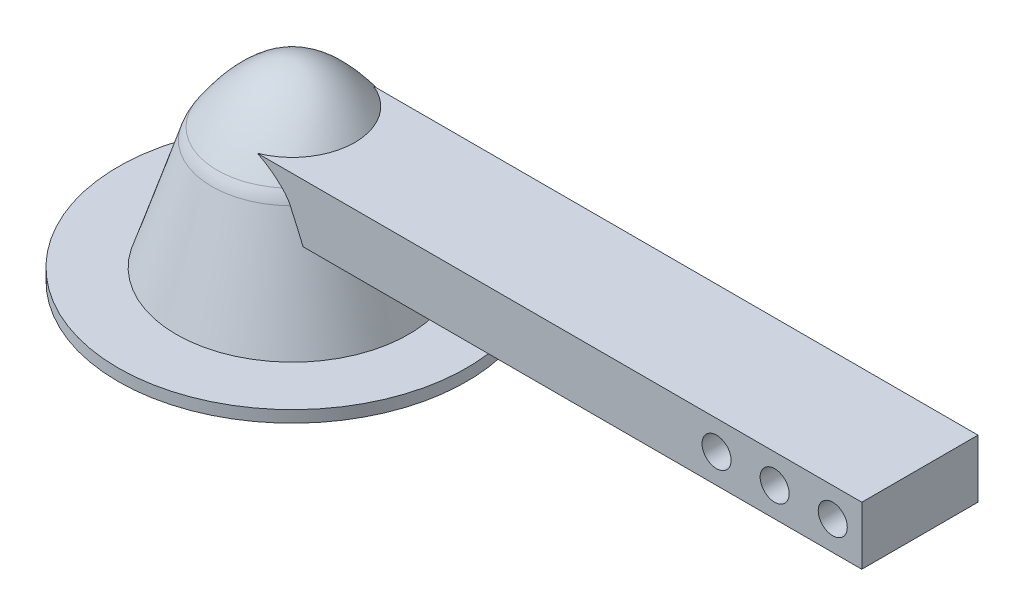
SolidWorks part; units mm, degrees
material "1060 Alloy"
ref_plane "Front Plane" through (0, 0, 0) normal (0, 0, 1) x (1, 0, 0)
ref_plane "Top Plane" through (0, 0, 0) normal (0, 1, 0) x (1, 0, 0)
ref_plane "Right Plane" through (0, 0, 0) normal (1, 0, 0) x (0, 0, -1)
sketch "Sketch1" plane through (0, 0, 0) normal (0, 0, 1) x (1, 0, 0)
  line L0 (0, 27.7021) -> (0, -45.7364) construction
  line L1 (-59.1227, 0) -> (59.4945, 0) construction
  line L2 (0, 20.093) -> (25.4, 20.093)
  line L3 (25.4, 20.093) -> (25.4, 13.743)
  line L4 (25.4, 13.743) -> (0, 13.743)
  line L5 (25.4, 20.093) -> (38.1, 20.093)
  line L6 (38.1, 20.093) -> (38.1, 22.6646)
  line L7 (38.1, 22.6646) -> (0, 22.6646)
  line L8 (0, 22.6646) -> (0, 13.743)
  line L9 (25.4, 22.6646) -> (17.2297, 48.0481)
  line L10 (17.2297, 48.0481) -> (0, 48.0481)
  line L11 (0, 48.0481) -> (0, 22.6646)
  dimension "D1" = 25.4
  dimension "D2" = 6.35
  dimension "D3" = 12.7
  dimension "D4" = 2.5716
  dimension "D5" = 25.4
revolve "Revolve1" add sketch "Sketch1" angle 360 about L0
sketch "Sketch2" plane through (0, 0, 0) normal (1, 0, 0) x (0, 0, -1)
  line L0 (17.2297, 48.0481) -> (-17.2297, 48.0481) construction
  line L1 (0, 0) -> (0, 77.5452) construction
  line L2 (0, 48.0481) -> (17.2297, 48.0481)
  line L3 (0, 61.7403) -> (0, 48.0481)
  spline S0 degree 2 poles (17.2297, 48.0481) (8.6148, 61.7403) (0, 61.7403) knots 0 0 0 0.5 0.5 0.5
revolve "Revolve2" add sketch "Sketch2" angle 360 about L1
fillet "Fillet1" radius 10.16 1 edges at (0, 48.0481, 17.2297)
ref_plane "Plane1" through (22.86, 0, 0) normal (1, 0, 0) x (0, 0, -1)
sketch "Sketch3" plane through (22.86, 0, 0) normal (1, 0, 0) x (0, 0, -1)
  line L0 (17.6369, 46.783) -> (-17.6369, 46.783) construction
  line L1 (-12.7, 53.133) -> (12.7, 53.133)
  line L2 (-12.7, 53.133) -> (-12.7, 40.433)
  line L3 (-12.7, 40.433) -> (12.7, 40.433)
  line L4 (12.7, 53.133) -> (12.7, 40.433)
  line L5 (-12.7, 53.133) -> (12.7, 40.433) construction
  line L6 (-12.7, 40.433) -> (12.7, 53.133) construction
  point P0 (0, 46.783)
  dimension "D1" = 12.7
  dimension "D2" = 25.4
extrude "Boss-Extrude1" add sketch "Sketch3" along normal blind 38.1 and the other way blind 20.32
sketch "Sketch4" plane through (60.96, 0, 0) normal (1, 0, 0) x (0, 0, -1)
  line L1 (-12.7, 40.433) -> (12.7, 40.433)
  line L2 (-12.7, 40.433) -> (-12.7, 53.133)
  line L3 (-12.7, 53.133) -> (12.7, 53.133)
  line L4 (12.7, 40.433) -> (12.7, 53.133)
extrude "Boss-Extrude2" add sketch "Sketch4" along normal blind 76.2
sketch "Sketch5" plane through (0, 0, -12.7) normal (0, 0, -1) x (-1, 0, 0)
  line L0 (-137.16, 40.433) -> (-137.16, 53.133) construction
  line L1 (-15.0347, 40.433) -> (-137.16, 40.433) construction
  circle A0 centre (-130.81, 46.783) radius 3.175
  circle A1 centre (-118.11, 46.783) radius 3.175
  circle A2 centre (-105.41, 46.783) radius 3.175
  dimension "D1" = 6.35
  dimension "D2" = 6.35
  dimension "D4" = 12.7
  dimension "D5" = 6.35
  dimension "D3" = 3
extrude "Cut-Extrude1" cut sketch "Sketch5" against normal through all
